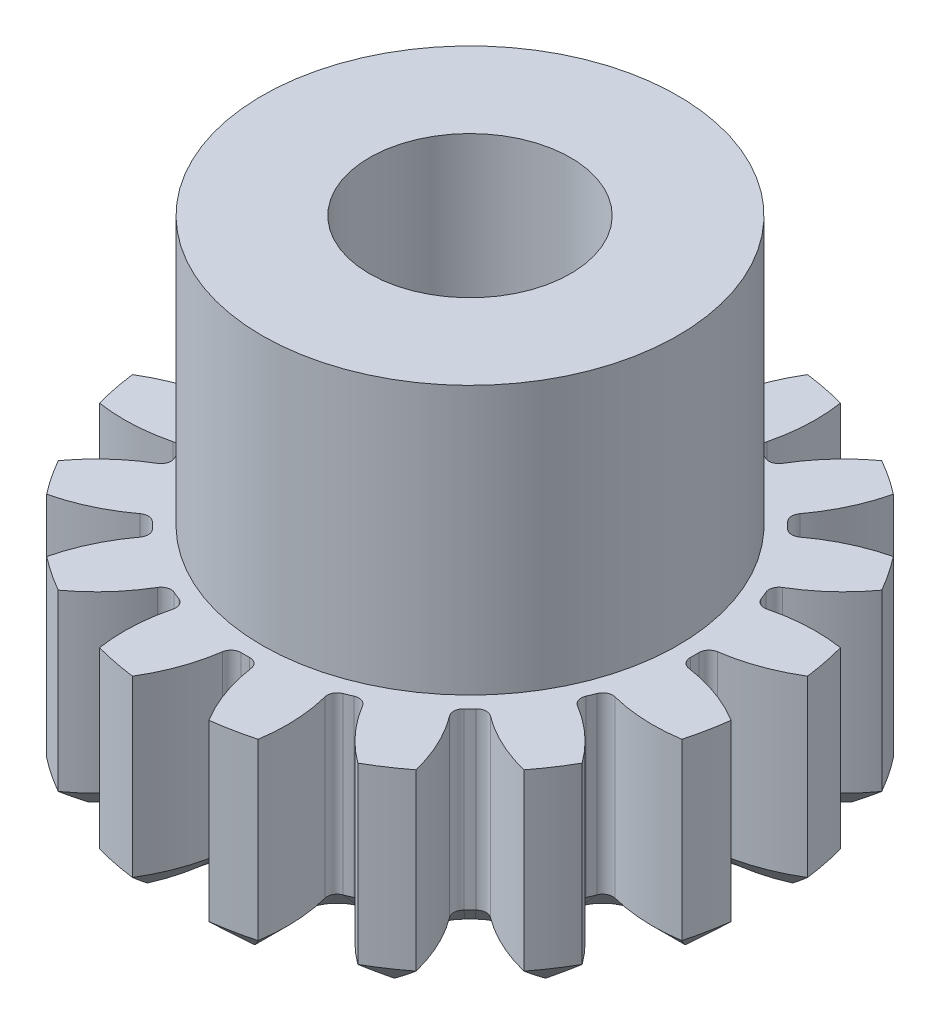
SolidWorks part; units mm, degrees
ref_plane "Front Plane" through (0, 0, 0) normal (0, 0, 1) x (1, 0, 0)
ref_plane "Top Plane" through (0, 0, 0) normal (0, 1, 0) x (1, 0, 0)
ref_plane "Right Plane" through (0, 0, 0) normal (1, 0, 0) x (0, 0, -1)
sketch "Sketch1" plane through (0, 0, 0) normal (0, 1, 0) x (1, 0, 0)
  circle A0 centre (0, 0) radius 4
  circle A1 centre (0, 0) radius 4.5
  circle A2 centre (0, 0) radius 3.3
  dimension "D1" = 8
  dimension "D2" = 9
  dimension "D3" = 1.2
extrude "Boss-Extrude1" add sketch "Sketch1" along normal mid plane 3 contours A1 A0 | A0 A2 | A2
sketch "Sketch3" plane through (0, 0, 0) normal (0, 1, 0) x (1, 0, 0)
  line L0 (0, 0) -> (0, 4.5) construction
  line L1 (-0.3921, 3.9807) -> (0.3921, 3.9807) construction
  line L2 (-0.2439, 3.291) -> (0, 0) construction
  line L3 (0, 2.9035) -> (-1.0108, 5.6808) construction
  line L4 (0, 0) -> (0.8779, 4.4135) construction
  line L5 (0.3921, 3.9807) -> (1.1611, 3.8278) construction
  circle A0 centre (0, 0) radius 4.5 construction
  circle A3 centre (0, 0) radius 3.3 construction
  circle A5 centre (0, 0) radius 4 construction
  circle A6 centre (0, 0) radius 4.5 construction
  arc A9 (1.6799, 5.4678) -> (-1.6799, 5.4678) centre (0, 0) ccw
  arc A10 (-1.6799, 5.4678) -> (-0.1982, 3.3441) centre (-2.8097, 3.1008) cw
  arc A11 (0.1982, 3.3441) -> (-0.1982, 3.3441) centre (0, 0) ccw
  arc A12 (1.6799, 5.4678) -> (0.1982, 3.3441) centre (2.8097, 3.1008) ccw
  point P6 (-1.8198, 5.4755)
  point P7 (-2.8097, 3.1008)
  point P9 (2.8097, 3.1008)
  point P10 (1.8198, 5.4755)
  point P11 (0.2439, 3.291)
  point P22 (0, 0)
  dimension "D2" = 20
  dimension "D3" = 11.25
extrude "Cut-Extrude1" cut sketch "Sketch3" against normal through all both and the other way through all
fillet "Fillet2" radius 0.15 2 edges at (0.1982, 0, -3.3441) (-0.1982, 0, -3.3441)
pattern_circular "CirPattern1" count 16 over 360 about axis through (0, 0, 0) along (0, 1, 0) of "Cut-Extrude1", "Fillet2"
sketch "Sketch4" plane through (0, 0, 0) normal (0, 1, 0) x (1, 0, 0)
  circle A0 centre (0, 0) radius 1.5
  dimension "D1" = 3
extrude "Cut-Extrude2" cut sketch "Sketch4" along normal through all both and the other way through all
sketch "Sketch5" plane through (0, 1.5, 0) normal (0, 1, 0) x (1, 0, 0)
  circle A0 centre (0, 0) radius 1.5
  circle A1 centre (0, 0) radius 3.1
  circle A2 centre (0, 0) radius 1.5 construction
  arc A4 (2.4129, 2.3239) -> (2.3239, 2.4129) centre (0, 0) ccw construction
  dimension "D1" = 0.25
extrude "Boss-Extrude2" add sketch "Sketch5" along normal blind 4
chamfer "Chamfer1" distance 0.4 angle 45 97 edges at (-2.5001, -1.5, -3.7416) (-2.5788, -1.5, -3.0622) (-2.2785, -1.5, -2.5087) (-2.3688, -1.5, -2.3688) (-2.5087, -1.5, -2.2785) (-3.0622, -1.5, -2.5788) (-3.7416, -1.5, -2.5001) (-3.5543, -1.5, -1.8422) (-3.0651, -1.5, -1.4458) (-3.095, -1.5, -1.282) (-3.1897, -1.5, -1.145) (-3.8159, -1.5, -1.2107) (-4.4135, -1.5, -0.8779) (-3.9888, -1.5, -0.3418) (-3.385, -1.5, -0.1628) (-3.35, -1.5, 0) (-3.385, -1.5, 0.1628) (-3.9888, -1.5, 0.3418) (-4.4135, -1.5, 0.8779) (-3.8159, -1.5, 1.2107) (-3.1897, -1.5, 1.145) (-3.095, -1.5, 1.282) (-3.0651, -1.5, 1.4458) (-3.5543, -1.5, 1.8422) (-3.7416, -1.5, 2.5001) (-3.0622, -1.5, 2.5788) (-2.5087, -1.5, 2.2785) (-2.3688, -1.5, 2.3688) (-2.2785, -1.5, 2.5087) (-2.5788, -1.5, 3.0622) (-2.5001, -1.5, 3.7416) (-1.8422, -1.5, 3.5543) (-1.4458, -1.5, 3.0651) (-1.282, -1.5, 3.095) (-1.145, -1.5, 3.1897) (-1.2107, -1.5, 3.8159) (-0.8779, -1.5, 4.4135) (-0.3418, -1.5, 3.9888) (-0.1628, -1.5, 3.385) (0, -1.5, 3.35) (0.1628, -1.5, 3.385) (0.3418, -1.5, 3.9888) (0.8779, -1.5, 4.4135) (1.2107, -1.5, 3.8159) (1.145, -1.5, 3.1897) (1.282, -1.5, 3.095) (1.4458, -1.5, 3.0651) (1.8422, -1.5, 3.5543) (2.5001, -1.5, 3.7416) (2.5788, -1.5, 3.0622) (2.2785, -1.5, 2.5087) (2.3688, -1.5, 2.3688) (2.5087, -1.5, 2.2785) (3.0622, -1.5, 2.5788) (3.7416, -1.5, 2.5001) (3.5543, -1.5, 1.8422) (3.0651, -1.5, 1.4458) (3.095, -1.5, 1.282) (3.1897, -1.5, 1.145) (3.8159, -1.5, 1.2107) (4.4135, -1.5, 0.8779) (3.9888, -1.5, 0.3418) (3.385, -1.5, 0.1628) (3.35, -1.5, 0) (3.385, -1.5, -0.1628) (3.9888, -1.5, -0.3418) (4.4135, -1.5, -0.8779) (3.8159, -1.5, -1.2107) (3.1897, -1.5, -1.145) (3.095, -1.5, -1.282) (3.0651, -1.5, -1.4458) (3.5543, -1.5, -1.8422) (3.7416, -1.5, -2.5001) (3.0622, -1.5, -2.5788) (2.5087, -1.5, -2.2785) (2.3688, -1.5, -2.3688) (2.2785, -1.5, -2.5087) (2.5788, -1.5, -3.0622) (2.5001, -1.5, -3.7416) (1.8422, -1.5, -3.5543) (1.4458, -1.5, -3.0651) (1.282, -1.5, -3.095) (1.145, -1.5, -3.1897) (1.2107, -1.5, -3.8159) (0.8779, -1.5, -4.4135) (0.3418, -1.5, -3.9888) (0.1628, -1.5, -3.385) (0, -1.5, -3.35) (-0.1628, -1.5, -3.385) (-0.3418, -1.5, -3.9888) (-0.8779, -1.5, -4.4135) (-1.2107, -1.5, -3.8159) (-1.145, -1.5, -3.1897) (-1.282, -1.5, -3.095) (-1.4458, -1.5, -3.0651) (-1.8422, -1.5, -3.5543) (0, -1.5, 1.5)
equation "\"Module\"= .5"
equation "\"Number of Teeth\"= 16"
equation "\"D1@Sketch1\"=\"Module\"* \"Number of Teeth\""
equation "\"D2@Sketch1\"=(\"Number of Teeth\" + 2) * \"Module\""
equation "\"D3@Sketch1\"=\"Module\" * if( \"Module\" => 1.25, 2.25, 2.4)"
equation "\"D3@Sketch3\"=180 / \"Number of Teeth\""
equation "\"D1@CirPattern1\"=\"Number of Teeth\""
equation "\"D1@Fillet2\"=.3 * \"Module\""
